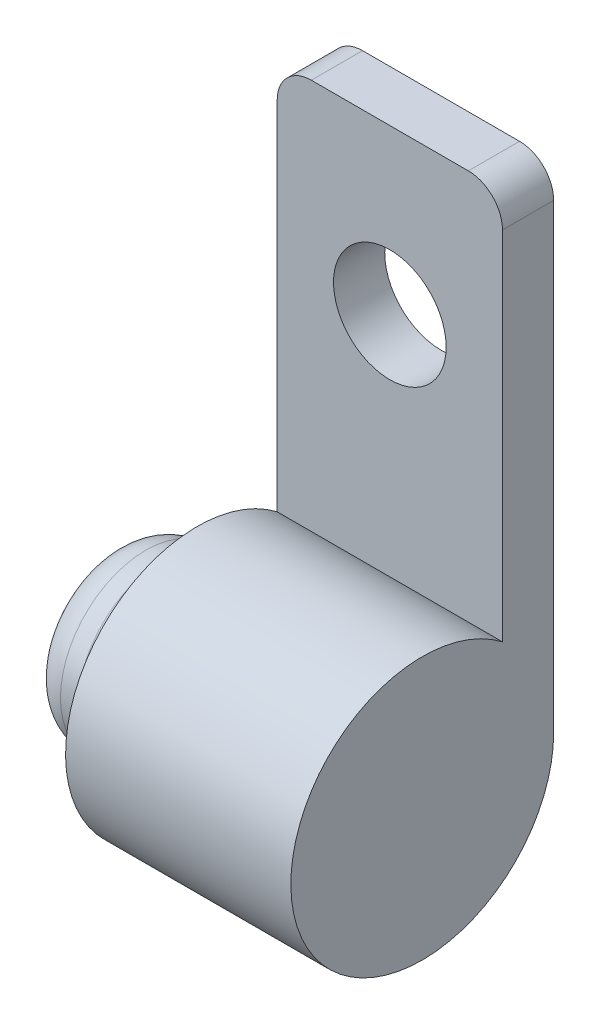
SolidWorks part; units mm, degrees
material "AISI 304"
ref_plane "前视基准面" through (0, 0, 0) normal (0, 0, 1) x (1, 0, 0)
ref_plane "上视基准面" through (0, 0, 0) normal (0, 1, 0) x (1, 0, 0)
ref_plane "右视基准面" through (0, 0, 0) normal (1, 0, 0) x (0, 0, -1)
other "Configuration Table"
sketch "草图1" plane through (0, 0, 0) normal (1, 0, 0) x (0, 0, -1)
  circle A0 centre (0, 0) radius 3.85
  dimension "D1" = 7.7
extrude "凸台-拉伸1" add sketch "草图1" along normal blind 6.6
sketch "草图2" plane through (0, 0, 0) normal (-1, 0, 0) x (0, 0, 1)
  line L0 (-3.85, 0) -> (-3.85, 14.5)
  line L1 (-3.85, 14.5) -> (-2.35, 14.5)
  line L2 (-2.35, 14.5) -> (-2.35, 3.0496)
  circle A0 centre (0, 0) radius 3.85 construction
  arc A1 (-2.35, 3.0496) -> (-3.85, 0) centre (0, 0) ccw
  dimension "D1" = 1.5
  dimension "D2" = 14.5
extrude "凸台-拉伸2" add sketch "草图2" against normal up to surface (6.6 mm away) up to face at (6.6, 0, -3.85)
sketch "草图3" plane through (0, 0, -2.35) normal (0, 0, 1) x (1, 0, 0)
  line L0 (3.3, 14.5) -> (3.3, 9.7) construction
  line L1 (6.6, 14.5) -> (0, 14.5) construction
  circle A0 centre (3.3, 9.7) radius 1.65
  dimension "D1" = 3.3
  dimension "D2" = 9.7
extrude "切除-拉伸1" cut sketch "草图3" against normal up to surface (1.5 mm away) up to face at (3.3, 7.25, -3.85)
sketch "草图4" plane through (0, 0, 0) normal (-1, 0, 0) x (0, 0, 1)
  circle A0 centre (0, 0) radius 2.5
  dimension "D1" = 5
extrude "凸台-拉伸3" add sketch "草图4" along normal offset from surface (2.5 mm away) 9.1 up to face at (6.6, 7.2064, -1.4613)
fillet "圆角1" radius 1 2 edges at (0, 0, 2.5) (-2.5, 0, -2.5)
fillet "圆角2" radius 1 2 edges at (6.6, 14.5, -3.1) (0, 14.5, -3.1)
